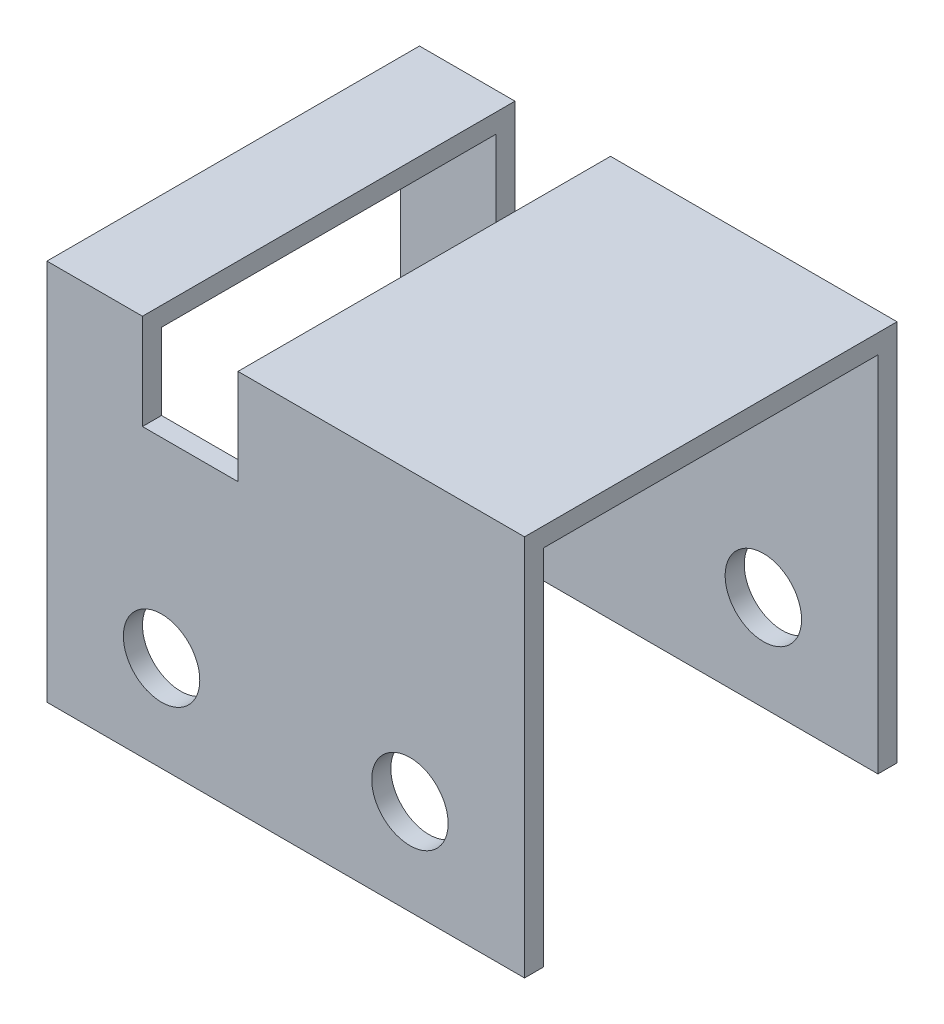
SolidWorks part; units mm, degrees
ref_plane "正面" through (0, 0, 0) normal (0, 0, 1) x (1, 0, 0)
ref_plane "平面" through (0, 0, 0) normal (0, 1, 0) x (1, 0, 0)
ref_plane "右側面" through (0, 0, 0) normal (1, 0, 0) x (0, 0, -1)
sketch "ｽｹｯﾁ1" plane through (0, 0, 0) normal (0, 0, 1) x (1, 0, 0)
  line L0 (-25, -37) -> (25, -37)
  line L2 (-25, -37) -> (-25, 3)
  line L4 (25, -37) -> (25, 3)
  line L5 (-25, 3) -> (-15, 3)
  line L6 (-15, 3) -> (-15, -7)
  line L7 (-15, -7) -> (-5, -7)
  line L8 (-5, -7) -> (-5, 3)
  line L9 (-5, 3) -> (25, 3)
  point P4 (0, -37)
  dimension "D1" = 50
  dimension "D2" = 40
  dimension "D3" = 3
  dimension "D4" = 10
  dimension "D5" = 10
  dimension "D6" = 10
extrude "Head-W" add sketch "ｽｹｯﾁ1" along normal mid plane 39
sketch "Head-t" plane through (25, 0, 0) normal (1, 0, 0) x (0, 0, -1)
  line L14 (-17.5, -37) -> (17.5, -37)
  line L17 (17.5, -37) -> (17.5, 1)
  line L18 (17.5, 1) -> (-17.5, 1)
  line L19 (-17.5, 1) -> (-17.5, -37)
  line L20 (17.5, -37) -> (17.5, 1)
  line L21 (17.5, 1) -> (-17.5, 1)
  line L22 (-17.5, 1) -> (-17.5, -37)
  dimension "D1" = 2
extrude "ｶｯﾄ - 押し出し1" cut sketch "Head-t" against normal through all
sketch "ｽｹｯﾁ3" plane through (0, 0, 19.5) normal (0, 0, 1) x (1, 0, 0)
  line L0 (-13, -27) -> (13, -27) construction
  line L2 (-25, -37) -> (25, -37) construction
  circle A0 centre (-13, -27) radius 4
  circle A1 centre (13, -27) radius 4
  point P4 (0, -27)
  dimension "D1" = 8
  dimension "D2" = 26
  dimension "D3" = 10
extrude "ｶｯﾄ - 押し出し2" cut sketch "ｽｹｯﾁ3" against normal through all
